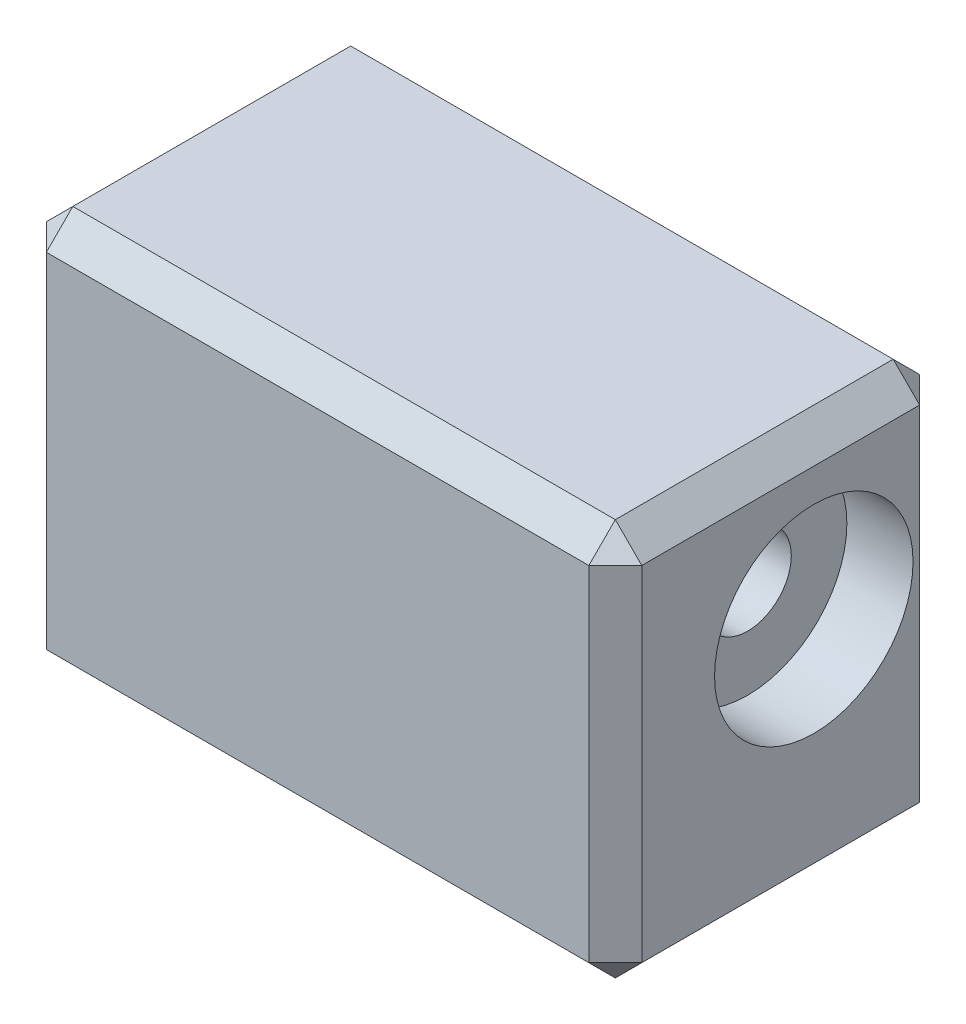
SolidWorks part; units mm, degrees
material "ABS"
ref_plane "Piano frontale" through (0, 0, 0) normal (0, 0, 1) x (1, 0, 0)
ref_plane "Piano superiore" through (0, 0, 0) normal (0, 1, 0) x (1, 0, 0)
ref_plane "Piano destro" through (0, 0, 0) normal (1, 0, 0) x (0, 0, -1)
sketch "Schizzo1" plane through (0, 0, 0) normal (0, 1, 0) x (1, 0, 0)
  line L1 (0, 0) -> (-45, 0)
  line L2 (0, 0) -> (0, 25)
  line L3 (0, 25) -> (-45, 25)
  line L4 (-45, 0) -> (-45, 25)
  dimension "D1" = 45
  dimension "D2" = 25
extrude "Estrusione-Estrusione1" add sketch "Schizzo1" along normal blind 30
sketch "Schizzo2" plane through (0, 0, -25) normal (0, 0, -1) x (-1, 0, 0)
  line L0 (22.5, 0) -> (22.5, 18) construction
  line L1 (0, 0) -> (45, 0) construction
  circle A0 centre (22.5, 18) radius 10
  dimension "D1" = 20
  dimension "D2" = 18
extrude "Taglio-Estrusione1" cut sketch "Schizzo2" against normal blind 18
hole_wizard "Foro lamato per Vite M6 a testa cilindrica-1" positions "Schizzo3" profile "Schizzo5" counterbore size "M6" standard "DIN"
sketch "Schizzo3" plane through (0, 0, 0) normal (1, 0, 0) x (0, 0, -1)
  line L0 (25, 30) -> (25, 0) construction
  line L2 (0, 0) -> (25, 0) construction
  point P1 (15, 18)
  dimension "D1" = 10
  dimension "D2" = 18
sketch "Schizzo5" plane through (0, 18, -15) normal (0, 1, 0) x (0, 0, -1)
  line L0 (0, 0) -> (0, 81.9828)
  line L1 (0, 81.9828) -> (3.3, 80)
  line L2 (3.3, 80) -> (3.3, 5)
  line L3 (3.3, 5) -> (7.5, 5)
  line L4 (7.5, 5) -> (7.5, 0)
  line L5 (7.5, 0) -> (0, 0)
  line L10 (0, 81.9828) -> (-3.3, 80) construction
  line L11 (0, -6.35) -> (0, 107.95) construction
  dimension "Hole Dia." = 6.6
  dimension "Hole Depth" = 80
  dimension "C'Bore Dia." = 15
  dimension "C'Bore Depth" = 5
  dimension "Drill Angle" = 118
chamfer "Smusso1" distance 2 angle 45 12 edges at (0, 30, -12.5) (-22.5, 30, 0) (0, 15, 0) (-22.5, 0, 0) (0, 0, -12.5) (0, 15, -25) (-22.5, 30, -25) (-22.5, 0, -25) (-45, 0, -12.5) (-45, 15, 0) (-45, 30, -12.5) (-45, 15, -25)
sketch "Schizzo6" plane through (-45, 0, 0) normal (-1, 0, 0) x (0, 0, 1)
  circle A0 centre (-15, 18) radius 6
  dimension "D1" = 12
extrude "Taglio-Estrusione2" cut sketch "Schizzo6" against normal blind 3
